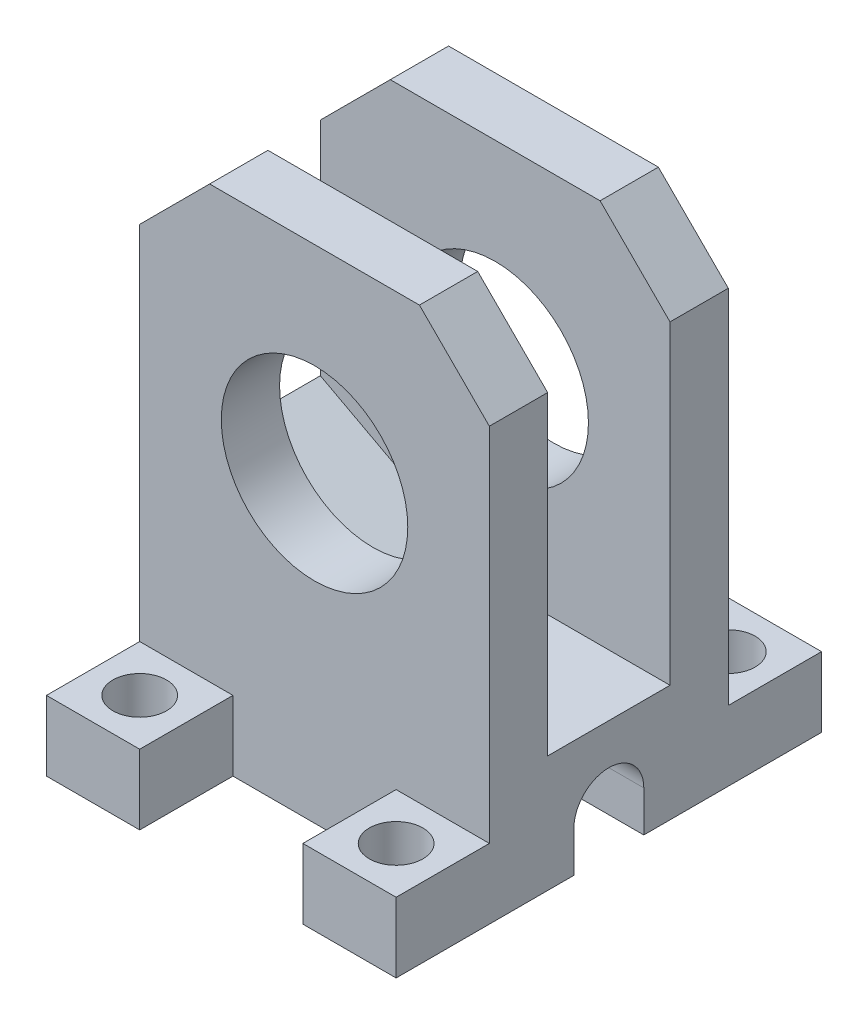
SolidWorks part; units mm, degrees
ref_plane "Plan de face" through (0, 0, 0) normal (0, 0, 1) x (1, 0, 0)
ref_plane "Plan de dessus" through (0, 0, 0) normal (0, 1, 0) x (1, 0, 0)
ref_plane "Plan de droite" through (0, 0, 0) normal (1, 0, 0) x (0, 0, -1)
sketch "Esquisse1" plane through (0, 0, 0) normal (0, 0, 1) x (1, 0, 0)
  line L0 (0, 0) -> (15, 0)
  line L1 (0, 0) -> (-15, 0)
  line L2 (-15, 0) -> (-15, 45)
  line L3 (-15, 45) -> (15, 45)
  line L4 (15, 45) -> (15, 0)
  line L5 (0, 0) -> (0, 28) construction
  circle A0 centre (0, 28) radius 8
  dimension "D1" = 28
extrude "Boss.-Extru.1" add sketch "Esquisse1" against normal blind 5
sketch "Esquisse2" plane through (0, 0, -5) normal (0, 0, -1) x (-1, 0, 0)
  line L0 (-15, 0) -> (15, 0)
  line L1 (15, 0) -> (15, 12)
  line L2 (15, 45) -> (15, 0) construction
  line L3 (15, 12) -> (-15, 12)
  line L4 (-15, 0) -> (-15, 45) construction
  line L5 (-15, 12) -> (-15, 0)
extrude "Boss.-Extru.2" add sketch "Esquisse2" along normal blind 10.5
sketch "Esquisse4" plane through (0, 0, 0) normal (0, -1, 0) x (1, 0, 0)
  line L0 (-15, -15.5) -> (15, -15.5)
  line L1 (15, -15.5) -> (15, -20.5)
  line L2 (15, -20.5) -> (-15, -20.5)
  line L3 (-15, -20.5) -> (-15, -15.5)
extrude "Boss.-Extru.3" add sketch "Esquisse4" against normal blind 45
sketch "Esquisse6" plane through (0, 0, -20.5) normal (0, 0, -1) x (-1, 0, 0)
  line L0 (0, 0) -> (0, 28) construction
  circle A1 centre (0, 28) radius 8
extrude "Enlèv. mat.-Extru.3" cut sketch "Esquisse6" against normal blind 10
sketch "Esquisse8" plane through (0, 0, 0) normal (0, -1, 0) x (1, 0, 0)
  line L0 (-15, 0) -> (-15, 8)
  line L1 (-15, 8) -> (-7, 8)
  line L2 (-7, 8) -> (-7, 0)
  line L3 (-15, 0) -> (15, 0) construction
  line L4 (-15, 0) -> (-7, 0)
  line L5 (15, 0) -> (15, 8)
  line L6 (15, 8) -> (7, 8)
  line L7 (7, 8) -> (7, 0)
  line L8 (7, 0) -> (15, 0)
  line L9 (-15, -20.5) -> (-15, -28.5)
  line L10 (-15, -28.5) -> (-7, -28.5)
  line L11 (-7, -28.5) -> (-7, -20.5)
  line L12 (-15, -20.5) -> (15, -20.5) construction
  line L13 (-7, -20.5) -> (-15, -20.5)
  line L14 (15, -20.5) -> (15, -28.5)
  line L15 (15, -28.5) -> (7, -28.5)
  line L16 (7, -28.5) -> (7, -20.5)
  line L17 (7, -20.5) -> (15, -20.5)
  line L18 (15, -28.5) -> (7, -20.5) construction
  line L19 (7, -28.5) -> (15, -20.5) construction
  line L20 (7, 8) -> (15, 0) construction
  line L21 (7, 0) -> (15, 8) construction
  line L22 (-15, 8) -> (-7, 0) construction
  line L23 (-7, 8) -> (-15, 0) construction
  line L24 (-15, -20.5) -> (-7, -28.5) construction
  line L25 (-15, -28.5) -> (-7, -20.5) construction
  circle A0 centre (-11, 4) radius 2.3
  circle A2 centre (11, -24.5) radius 2.3
  circle A3 centre (-11, -24.5) radius 2.3
  circle A4 centre (11, 4) radius 2.3
extrude "Boss.-Extru.4" add sketch "Esquisse8" against normal blind 8
sketch "Esquisse9" plane through (0, 0, 0) normal (0, -1, 0) x (1, 0, 0)
  line L0 (-15, 8) -> (-15, -28.5)
  line L1 (-15, -28.5) -> (-7, -28.5)
  line L2 (-7, -28.5) -> (-7, -20.5)
  line L3 (-7, -20.5) -> (7, -20.5)
  line L4 (7, -20.5) -> (7, -28.5)
  line L5 (7, -28.5) -> (15, -28.5)
  line L6 (15, -28.5) -> (15, 8)
  line L7 (15, 8) -> (7, 8)
  line L8 (7, 8) -> (7, 0) construction
  line L9 (15, 8) -> (7, 8) construction
  line L10 (7, 8) -> (7, 0)
  line L11 (7, 0) -> (-7, 0)
  line L12 (-7, 0) -> (-7, 8)
  line L13 (-7, 8) -> (-15, 8)
extrude "Enlèv. mat.-Extru.4" cut sketch "Esquisse9" against normal blind 2
sketch "Esquisse10" plane through (-15, 0, 0) normal (-1, 0, 0) x (0, 0, 1)
  line L0 (-10.25, 2) -> (-10.25, 5.5) construction
  line L1 (8, 2) -> (-28.5, 2) construction
  line L2 (-13.25, 5.5) -> (-13.25, 2)
  line L3 (-13.25, 2) -> (-7.25, 2)
  line L4 (-7.25, 2) -> (-7.25, 5.5)
  circle A0 centre (-10.25, 5.5) radius 3
extrude "Enlèv. mat.-Extru.5" cut sketch "Esquisse10" against normal blind 50
sketch "Esquisse11" plane through (0, 0, 0) normal (0, 0, 1) x (1, 0, 0)
  line L0 (-15, 45) -> (-15, 39)
  line L1 (-15, 45) -> (-15, 8) construction
  line L2 (-15, 45) -> (-9, 45)
  line L3 (15, 45) -> (-15, 45) construction
  line L4 (-9, 45) -> (-15, 39)
  line L5 (15, 45) -> (9, 45)
  line L6 (9, 45) -> (15, 45)
  line L7 (15, 45) -> (15, 39)
  line L8 (15, 8) -> (15, 45) construction
  line L9 (15, 39) -> (9, 45)
  line M8 (15, 8) -> (15, 45)
  line M9 (15, 45) -> (-15, 45)
  line M10 (-15, 45) -> (-15, 8)
extrude "Enlèv. mat.-Extru.6" cut sketch "Esquisse11" against normal blind 50 contours L4 M9 M10 | L9 M8 M9
sketch "Esquisse12" plane through (0, 0, -5) normal (0, 0, -1) x (-1, 0, 0)
  line L0 (0, 20) -> (0, 12) construction
  line L1 (0, 12) -> (15, 12)
  line L2 (15, 39) -> (15, 8) construction
  line L3 (15, 12) -> (15, 20)
  line L4 (15, 20) -> (0, 12)
  circle A0 centre (0, 28) radius 8 construction
extrude "Boss.-Extru.5" add sketch "Esquisse12" along normal blind 10.5
